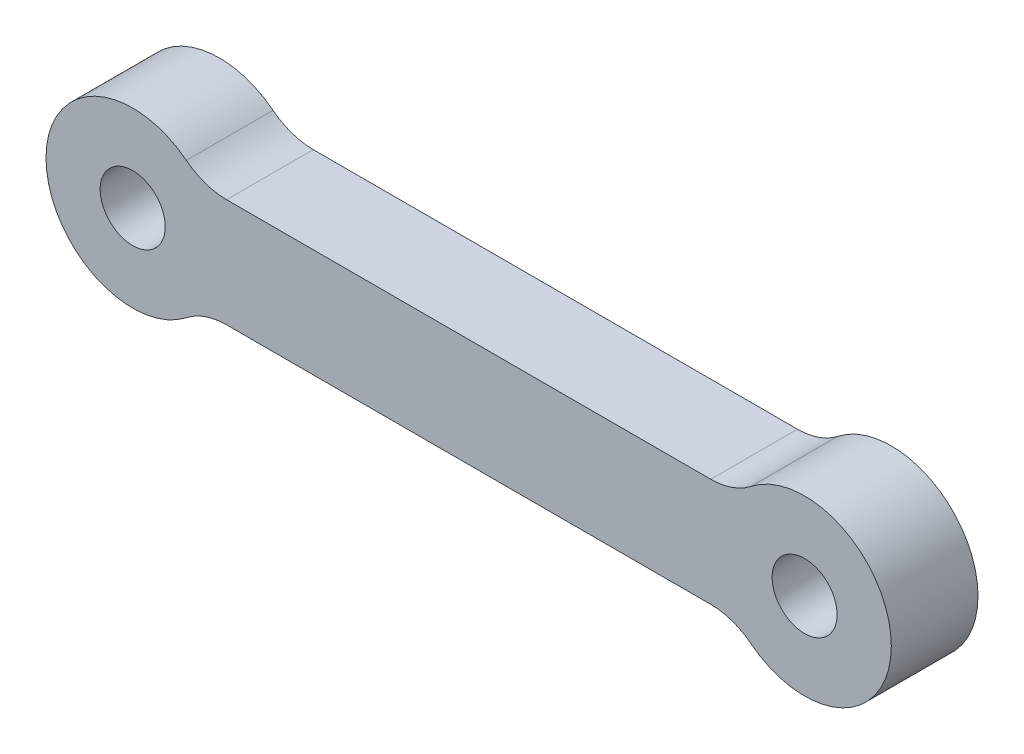
SolidWorks part; units mm, degrees
ref_plane "Front Plane" through (0, 0, 0) normal (0, 0, 1) x (1, 0, 0)
ref_plane "Top Plane" through (0, 0, 0) normal (0, 1, 0) x (1, 0, 0)
ref_plane "Right Plane" through (0, 0, 0) normal (1, 0, 0) x (0, 0, -1)
sketch "Sketch2" plane through (0, 0, 0) normal (0, 0, 1) x (1, 0, 0)
  line L0 (0, 0) -> (0, 4.8209) construction
  line L1 (-15.5, 0) -> (-14, 0) construction
  line L2 (0, 0) -> (15.5, 0) construction
  line L3 (-11.1699, 2.5) -> (11.1699, 2.5)
  line L5 (-11.1699, -2.5) -> (11.1699, -2.5)
  line L7 (-12.3775, 2.5) -> (12.3775, -2.5) construction
  line L8 (-12.3775, -2.5) -> (12.3775, 2.5) construction
  circle A0 centre (-15.5, 0) radius 1.5
  arc A1 (-13.0256, 3.1429) -> (-13.0256, -3.1429) centre (-15.5, 0) ccw
  circle A2 centre (15.5, 0) radius 1.5
  arc A3 (13.0256, 3.1429) -> (13.0256, -3.1429) centre (15.5, 0) cw
  arc A4 (11.1699, -2.5) -> (13.0256, -3.1429) centre (11.1699, -5.5) cw
  arc A5 (11.1699, 2.5) -> (13.0256, 3.1429) centre (11.1699, 5.5) ccw
  arc A6 (-13.0256, -3.1429) -> (-11.1699, -2.5) centre (-11.1699, -5.5) cw
  arc A7 (-11.1699, 2.5) -> (-13.0256, 3.1429) centre (-11.1699, 5.5) cw
  point P5 (0, 0)
  dimension "D2" = 3
  dimension "D3" = 8
  dimension "D5" = 3
  dimension "D1" = 31
  dimension "D4" = 5
extrude "Boss-Extrude1" add sketch "Sketch2" along normal blind 4
